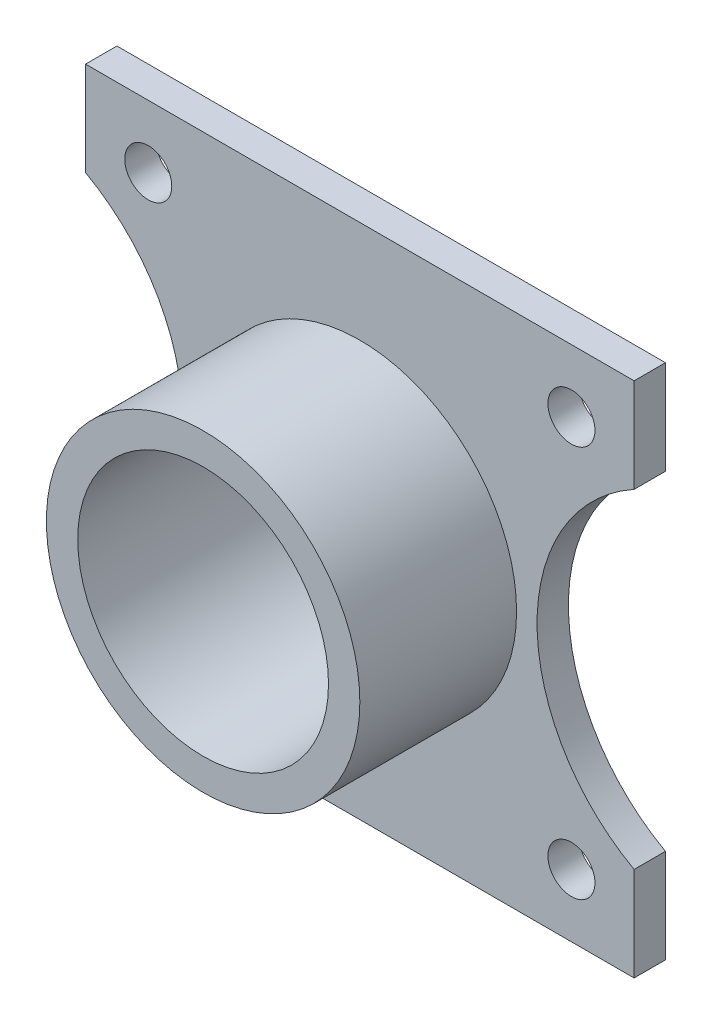
SolidWorks part; units mm, degrees
ref_plane "前视基准面" through (0, 0, 0) normal (0, 0, 1) x (1, 0, 0)
ref_plane "上视基准面" through (0, 0, 0) normal (0, 1, 0) x (1, 0, 0)
ref_plane "右视基准面" through (0, 0, 0) normal (1, 0, 0) x (0, 0, -1)
other "Configuration Table"
sketch "草图1" plane through (0, 0, 0) normal (0, 0, 1) x (1, 0, 0)
  line L0 (-17.5, 16.5) -> (17.5, 16.5)
  line L1 (-13.5, 12.5) -> (13.5, 12.5) construction
  line L2 (-13.5, 12.5) -> (-13.5, -12.5) construction
  line L3 (-13.5, -12.5) -> (13.5, -12.5) construction
  line L4 (13.5, 12.5) -> (13.5, -12.5) construction
  line L5 (0, -12.5) -> (0, 12.5) construction
  line L6 (-13.5, 0) -> (13.5, 0) construction
  line L7 (17.5, 16.5) -> (17.5, -16.5)
  line L8 (17.5, -16.5) -> (-17.5, -16.5)
  line L9 (-17.5, -16.5) -> (-17.5, 16.5)
  line L10 (-17.5, 10.5) -> (-17.5, -10.5)
  line L11 (17.5, 10.5) -> (17.5, -10.5)
  circle A0 centre (13.5, 12.5) radius 1.5
  circle A1 centre (-13.5, 12.5) radius 1.5
  circle A2 centre (-13.5, -12.5) radius 1.5
  circle A3 centre (13.5, -12.5) radius 1.5
  circle A4 centre (0, 0) radius 8
  arc A6 (-17.5, 10.5) -> (-17.5, -10.5) centre (-23.3095, 0) cw
  arc A7 (17.5, 10.5) -> (17.5, -10.5) centre (23.3095, 0) ccw
  point P0 (0, 0)
  dimension "D3" = 3
  dimension "D4" = 3
  dimension "D5" = 3
  dimension "D6" = 3
  dimension "D7" = 16
  dimension "D15" = 12
  dimension "D1" = 25
  dimension "D2" = 27
  dimension "D9" = 4
  dimension "D10" = 4
  dimension "D11" = 4
  dimension "D12" = 4
  dimension "D13" = 6
  dimension "D14" = 6
extrude "凸台-拉伸1" add sketch "草图1" along normal blind 2
sketch "草图3" plane through (0, 0, 2) normal (0, 0, 1) x (1, 0, 0)
  circle A0 centre (0, 0) radius 10
  circle A1 centre (0, 0) radius 8 construction
  circle A2 centre (0, 0) radius 8
  dimension "D1" = 20
extrude "凸台-拉伸2" add sketch "草图3" along normal blind 10
